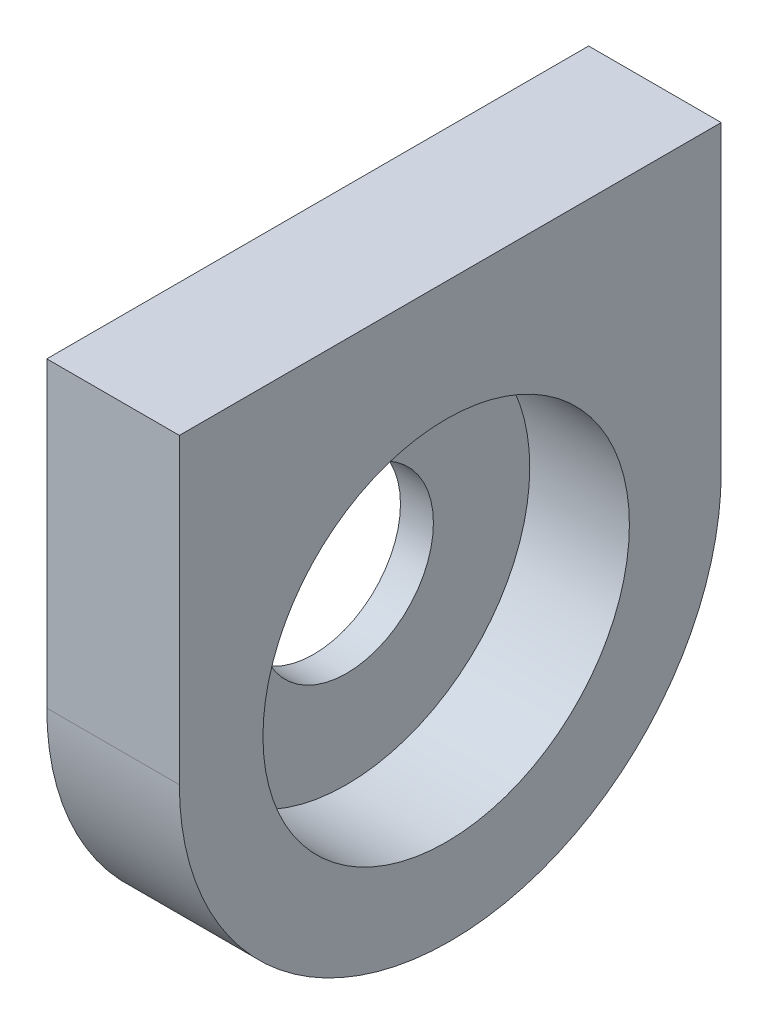
SolidWorks part; units mm, degrees
ref_plane "Alzado" through (0, 0, 0) normal (0, 0, 1) x (1, 0, 0)
ref_plane "Planta" through (0, 0, 0) normal (0, 1, 0) x (1, 0, 0)
ref_plane "Vista lateral" through (0, 0, 0) normal (1, 0, 0) x (0, 0, -1)
sketch "Croquis1" plane through (0, 0, 0) normal (1, 0, 0) x (0, 0, -1)
  line L4 (60.7, 0) -> (60.7, 3.3682)
  line B0 (-60.7, 0) -> (60.7, 0)
  line B1 (-93.6, 0) -> (-93.6, 3.3682)
  line B2 (-93.6, 3.3682) -> (93.6, 3.3682)
  line B3 (-93.6, 0) -> (-93.6, -15)
  line B4 (-60.7, -15) -> (-63.7, -15) construction
  line B5 (-93.6, 0) -> (-60.7, 0) construction
  line B6 (-60.7, -15) -> (-60.7, 0)
  line B7 (0, 3.3682) -> (0, 0) construction
  line B8 (93.6, 0) -> (60.7, 0) construction
  line B9 (93.6, 0) -> (93.6, 3.3682)
  line B10 (93.6, 0) -> (60.7, 0) construction
  line B11 (93.6, 0) -> (93.6, -15)
  line B12 (60.7, -15) -> (60.7, 0)
  arc B13 (-93.6, -15) -> (-60.7, -15) centre (-77.15, -15) ccw
  circle B14 centre (-76.9, -15) radius 13.2 construction
  circle B15 centre (-76.9, -23.5) radius 1.75
  circle B16 centre (-85.4, -15) radius 1.75
  circle B17 centre (-68.4, -15) radius 1.75
  circle B18 centre (-76.9, -6.5) radius 1.75
  circle B19 centre (-76.9, -15) radius 4
  circle B20 centre (76.9, -15) radius 5.275
  arc B21 (93.6, -15) -> (60.7, -15) centre (77.15, -15) cw
sketch_block_instance "Bloque1-1"
sketch_block "Bloque1"
extrude "Saliente-Extruir1" add sketch "Croquis1" along normal blind 2 contours B21 B11 B9 B2 L4 B12 B20
sketch "Croquis2" plane through (2, 0, 0) normal (1, 0, 0) x (0, 0, -1)
  line L3 (93.6, -15) -> (93.6, 3.3682)
  line L4 (93.6, 3.3682) -> (60.7, 3.3682)
  line L5 (60.7, 3.3682) -> (60.7, -15)
  line L6 (93.6, -15) -> (93.6, 3.3682)
  line L7 (93.6, 3.3682) -> (60.7, 3.3682)
  line L8 (60.7, 3.3682) -> (60.7, -15)
  circle A0 centre (76.9, -15) radius 11.125
  arc A2 (60.7, -15) -> (93.6, -15) centre (77.15, -15) ccw
  arc A3 (60.7, -15) -> (93.6, -15) centre (77.15, -15) ccw
  dimension "D1" = 22.25
  dimension "D2" = 0
extrude "Saliente-Extruir2" add sketch "Croquis2" along normal blind 6.05
